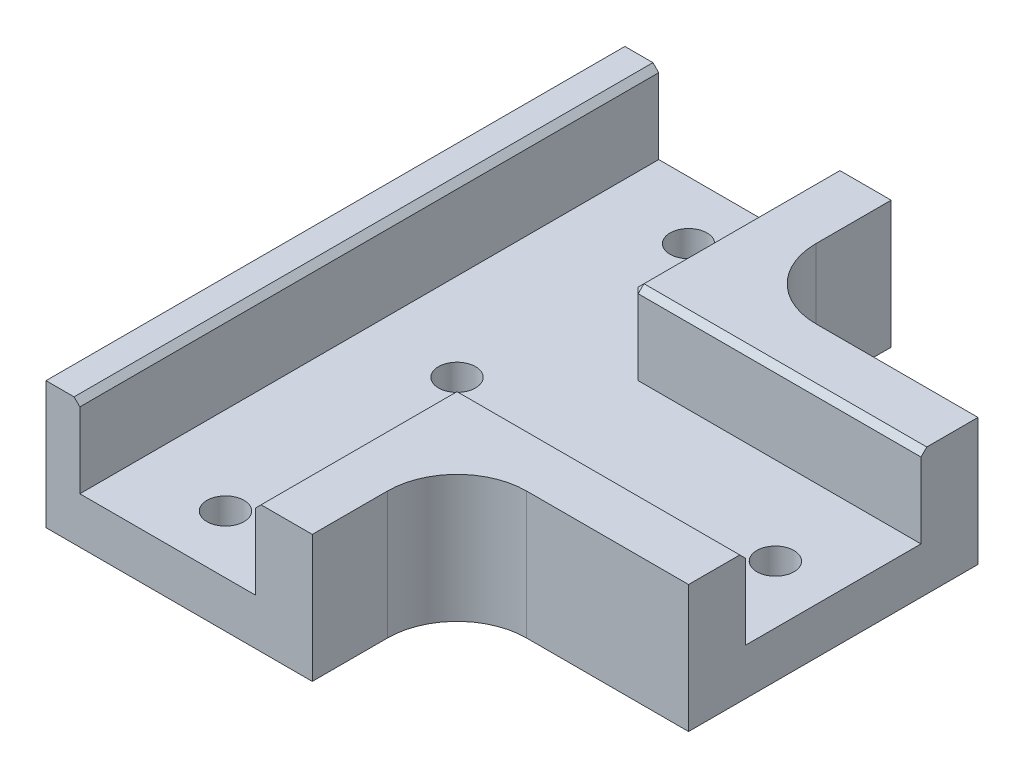
SolidWorks part; units mm, degrees
material "PLA"
ref_plane "前视基准面" through (0, 0, 0) normal (0, 0, 1) x (1, 0, 0)
ref_plane "上视基准面" through (0, 0, 0) normal (0, 1, 0) x (1, 0, 0)
ref_plane "右视基准面" through (0, 0, 0) normal (1, 0, 0) x (0, 0, -1)
sketch "草图1" plane through (0, 0, 0) normal (0, 1, 0) x (1, 0, 0)
  line L0 (0.6404, 0) -> (32.5, 0) construction
  line L1 (0, 25) -> (0, -25) construction
  line L2 (-10.5, 25) -> (12.5, 25)
  line L3 (12.5, 25) -> (12.5, 12.5)
  line L4 (12.5, 12.5) -> (32.5, 12.5)
  line L5 (32.5, 12.5) -> (32.5, -12.5)
  line L6 (32.5, -12.5) -> (12.5, -12.5)
  line L7 (12.5, -12.5) -> (12.5, -25)
  line L8 (12.5, -25) -> (-10.5, -25)
  line L10 (-7.5, 25) -> (-7.5, -25) construction
  line L11 (7.5, 25) -> (7.5, 7.5) construction
  line L12 (7.5, 7.5) -> (32.5, 7.5) construction
  line L13 (32.5, -7.5) -> (7.5, -7.5) construction
  line L14 (7.5, -7.5) -> (7.5, -25) construction
  line L15 (-10.5, 25) -> (-10.5, -25)
  dimension "D1" = 5
  dimension "D2" = 15
  dimension "D3" = 15
  dimension "D4" = 25
  dimension "D5" = 50
  dimension "D6" = 5
  dimension "D7" = 3
extrude "凸台-拉伸1" add sketch "草图1" along normal blind 4
sketch "草图2" plane through (0, 4, 0) normal (0, 1, 0) x (1, 0, 0)
  line L0 (12.5, 25) -> (-10.5, 25) construction
  line L1 (-5.575, 20.075) -> (-5.575, -20.075) construction
  line L2 (7.575, -25) -> (7.575, -7.575)
  line L3 (7.575, -7.575) -> (32.5, -7.575)
  line L4 (7.575, -25) -> (12.5, -25)
  line L5 (32.5, 7.575) -> (7.575, 7.575)
  line L6 (7.575, 7.575) -> (7.575, 25)
  line L7 (7.575, 7.575) -> (7.575, 20.075) construction
  line L8 (32.5, -12.5) -> (32.5, 12.5)
  line L9 (32.5, 12.5) -> (12.5, 12.5)
  line L10 (12.5, 12.5) -> (12.5, 25)
  line L11 (12.5, 25) -> (-10.5, 25)
  line L12 (-10.5, 25) -> (-10.5, -25)
  line L13 (-10.5, -25) -> (12.5, -25)
  line L14 (12.5, -25) -> (12.5, -12.5)
  line L15 (12.5, -12.5) -> (32.5, -12.5)
  line L16 (32.5, -12.5) -> (32.5, -7.575)
  line L17 (32.5, 12.5) -> (12.5, 12.5)
  line L18 (12.5, 12.5) -> (12.5, 25)
  line L19 (12.5, 25) -> (7.575, 25)
  line L20 (-10.5, 25) -> (-10.5, -25)
  line L21 (-10.5, -25) -> (-7.575, -25)
  line L22 (12.5, -25) -> (12.5, -12.5)
  line L23 (12.5, -12.5) -> (32.5, -12.5)
  line L24 (7.575, 20.075) -> (-5.575, 20.075) construction
  line L25 (-5.575, -20.075) -> (7.575, -20.075) construction
  line L26 (27.575, 7.575) -> (7.575, 7.575) construction
  line L27 (7.575, -7.575) -> (27.575, -7.575) construction
  line L28 (7.575, -20.075) -> (7.575, -7.575) construction
  line L29 (32.5, 7.575) -> (32.5, 12.5)
  line L30 (32.5, -12.5) -> (32.5, 12.5) construction
  line L31 (27.575, -7.575) -> (27.575, 7.575) construction
  line L32 (-10.5, -25) -> (12.5, -25) construction
  line L33 (-7.575, 25) -> (-10.5, 25)
  line L34 (12.5, 25) -> (-10.5, 25) construction
  line L35 (-7.575, 25) -> (-7.575, -25)
  line L44 (-10.5, 25) -> (-10.5, -25) construction
  dimension "D2" = 15.15
  dimension "D3" = 15.15
  dimension "D1" = 0
extrude "凸台-拉伸2" add sketch "草图2" along normal blind 7
sketch "草图3" plane through (0, 4, 0) normal (0, 1, 0) x (1, 0, 0)
  line L0 (0, 25) -> (0, -25) construction
  line L1 (7.575, 25) -> (-7.575, 25) construction
  line L2 (-7.575, -25) -> (7.575, -25) construction
  line L3 (0, 0) -> (32.5, 0) construction
  line L4 (32.5, -7.575) -> (32.5, 7.575) construction
  circle A0 centre (0, 0) radius 1.6
  circle A1 centre (0, 20) radius 1.6
  circle A2 centre (0, -20) radius 1.6
  circle A3 centre (27.5, 0) radius 1.6
  dimension "D1" = 3.2
  dimension "D2" = 20
  dimension "D3" = 27.5
extrude "切除-拉伸1" cut sketch "草图3" against normal through all
chamfer "倒角1" distance 0.5 angle 45 7 edges at (7.575, 11, 16.2875) (20.0375, 11, 7.575) (-7.575, 11, 0) (7.575, 11, -16.2875) (20.0375, 11, -7.575) (7.575, 7.5, 7.575) (7.575, 7.5, -7.575)
fillet "圆角1" radius 6 2 edges at (12.5, 5.5, -12.5) (12.5, 5.5, 12.5)
